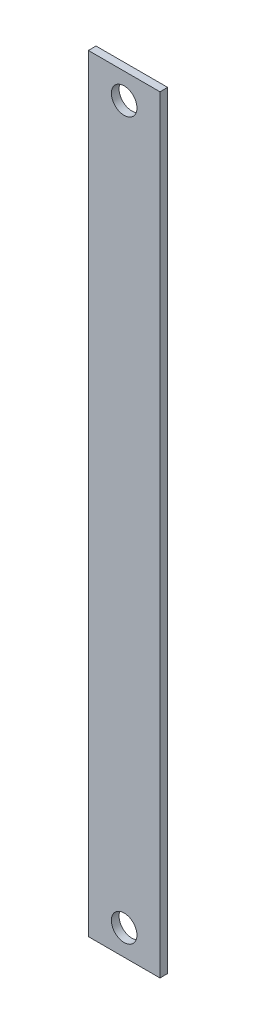
SolidWorks part; units mm, degrees
material "7075-T6 (SN)"
ref_plane "Alzado" through (0, 0, 0) normal (0, 0, 1) x (1, 0, 0)
ref_plane "Planta" through (0, 0, 0) normal (0, 1, 0) x (1, 0, 0)
ref_plane "Vista lateral" through (0, 0, 0) normal (1, 0, 0) x (0, 0, -1)
sketch "Croquis1" plane through (0, 0, 0) normal (0, 0, 1) x (1, 0, 0)
  line L1 (14, -150) -> (-14, -150)
  line L2 (14, -150) -> (14, 150)
  line L3 (14, 150) -> (-14, 150)
  line L4 (-14, -150) -> (-14, 150)
  line L5 (14, -150) -> (-14, 150) construction
  line L6 (14, 150) -> (-14, -150) construction
  point P0 (0, 0)
  dimension "D1" = 300
  dimension "D2" = 28
extrude "Saliente-Extruir1" add sketch "Croquis1" along normal mid plane 3
sketch "Croquis2" plane through (0, 0, -1.5) normal (0, 0, -1) x (-1, 0, 0)
  line L0 (0, 150) -> (0, 140) construction
  line L1 (-14, 150) -> (14, 150) construction
  line L2 (0, 0) -> (14, 0) construction
  line L3 (14, 150) -> (14, -150) construction
  circle A0 centre (0, 140) radius 5
  circle A1 centre (0, -140) radius 5
  dimension "D1" = 10
  dimension "D2" = 10
extrude "Cortar-Extruir1" cut sketch "Croquis2" against normal through all
